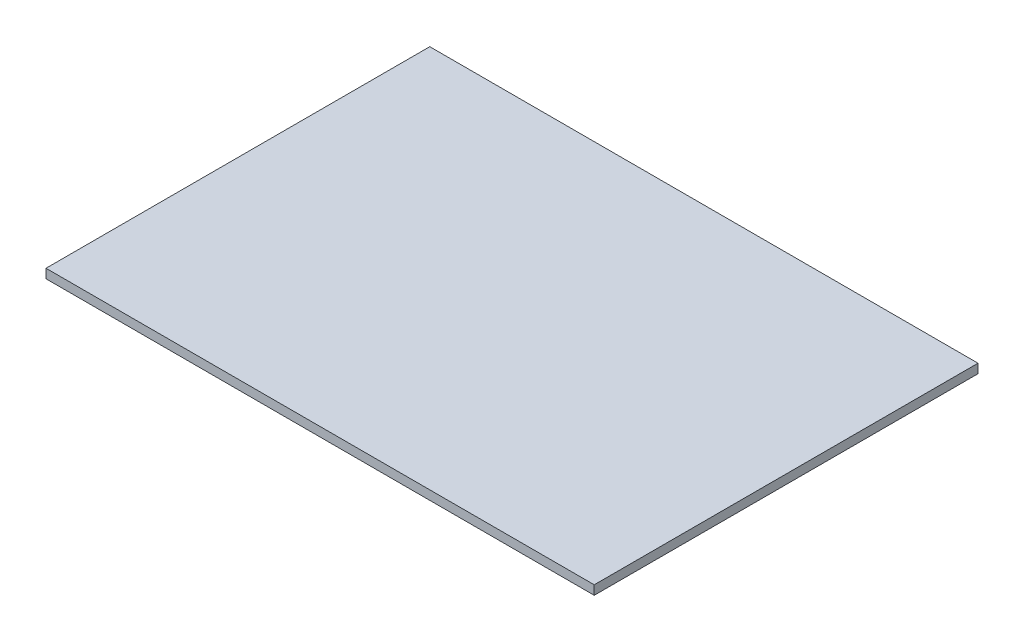
SolidWorks part; units mm, degrees
ref_plane "Front Plane" through (0, 0, 0) normal (0, 0, 1) x (1, 0, 0)
ref_plane "Top Plane" through (0, 0, 0) normal (0, 1, 0) x (1, 0, 0)
ref_plane "Right Plane" through (0, 0, 0) normal (1, 0, 0) x (0, 0, -1)
sketch "Sketch1" plane through (0, 0, 0) normal (0, 1, 0) x (1, 0, 0)
  line L1 (0, 533.4) -> (762, 533.4)
  line L2 (0, 533.4) -> (0, 0)
  line L3 (0, 0) -> (762, 0)
  line L4 (762, 533.4) -> (762, 0)
  line L5 (0, 533.4) -> (762, 0) construction
  line L6 (0, 0) -> (762, 533.4) construction
  point P0 (-2.6304, 18.4824)
  dimension "D1" = 533.4
  dimension "D2" = 762
extrude "Boss-Extrude1" add sketch "Sketch1" along normal blind 12.7
